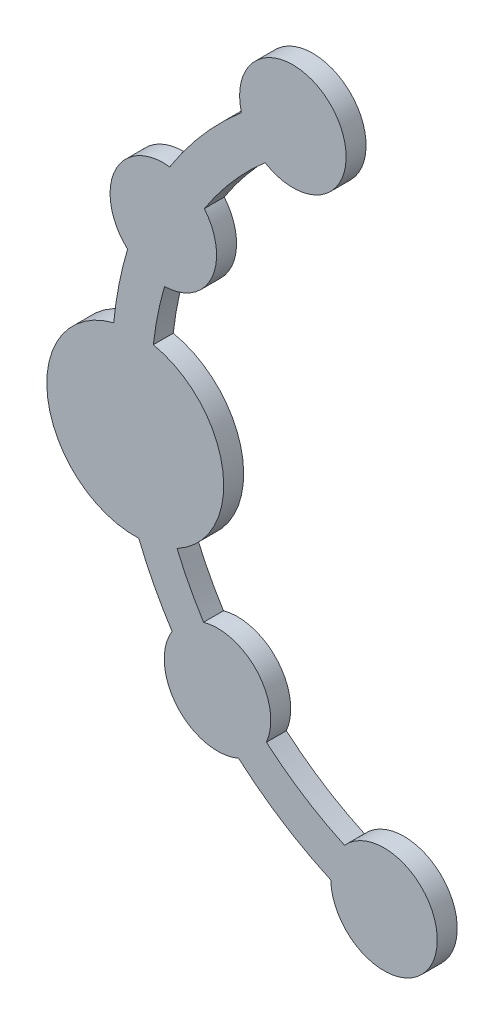
SolidWorks part; units mm, degrees
material "Copper"
ref_plane "Front Plane" through (0, 0, 0) normal (0, 0, 1) x (1, 0, 0)
ref_plane "Top Plane" through (0, 0, 0) normal (0, 1, 0) x (1, 0, 0)
ref_plane "Right Plane" through (0, 0, 0) normal (1, 0, 0) x (0, 0, -1)
sketch "Pads Sketch" plane through (0, 0, 0) normal (0, 0, 1) x (1, 0, 0)
  line L0 (0, 0) -> (-10.0698, -34.3025) construction
  line L1 (0, 0) -> (0, -35.75) construction
  line L2 (0, 0) -> (-10.0698, -34.3025) construction
  line L3 (0, 0) -> (-27.0136, -23.4164) construction
  line L4 (-35.3845, -5.099) -> (0, 0) construction
  circle A0 centre (0, 0) radius 35.75 construction
  circle A1 centre (-10.0698, -34.3025) radius 5.42
  circle A2 centre (-27.0136, -23.4164) radius 5.42
  circle A3 centre (-35.3845, -5.099) radius 5.42 [skipped]
  circle A4 centre (-32.5259, 14.8366) radius 5.42
  circle A5 centre (-19.3451, 30.0638) radius 5.42
  circle A6 centre (-35.3845, -5.099) radius 9
  dimension "D1" = 71.5
  dimension "D2" = 10.84
  dimension "D7" = 18
  dimension "D3" = 16.36
  dimension "D5" = 32.72
  dimension "D6" = 81.8
  dimension "D4" = 5
extrude "Pads" add sketch "Pads Sketch" along normal blind 2.03
sketch "Connector Sketch" plane through (0, 0, 2.03) normal (0, 0, 1) x (1, 0, 0)
  line L0 (-24.5782, 28.6527) -> (-22.176, 25.4418)
  line L1 (-14.0905, -30.6679) -> (-15.4883, -34.4264)
  arc A0 (-24.5782, 28.6527) -> (-15.4883, -34.4264) centre (0, 0) ccw
  circle A1 centre (-19.3451, 30.0638) radius 5.42 construction
  circle A2 centre (-10.0698, -34.3025) radius 5.42 construction
  arc A3 (-22.176, 25.4418) -> (-14.0905, -30.6679) centre (0, 0) ccw
  dimension "D1" = 37.75
  dimension "D2" = 33.75
extrude "Connector" add sketch "Connector Sketch" against normal blind 2.03
